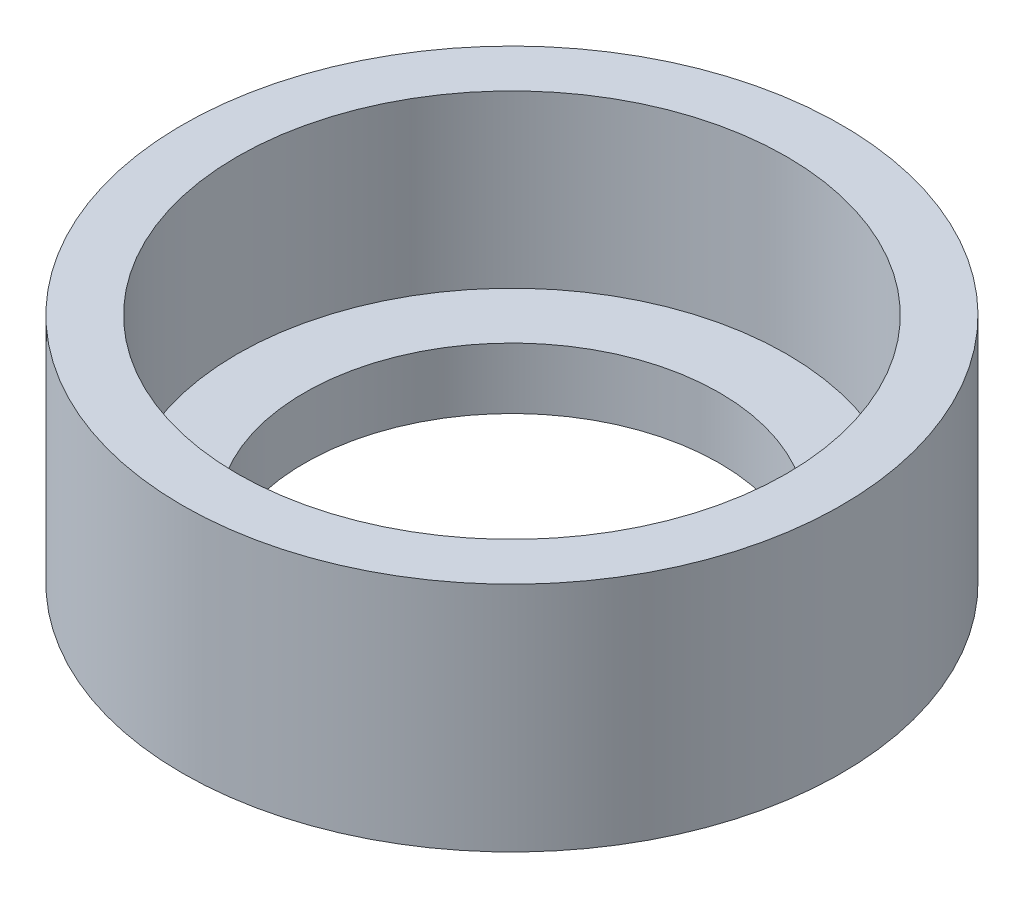
SolidWorks part; units mm, degrees
ref_plane "Front Plane" through (0, 0, 0) normal (0, 0, 1) x (1, 0, 0)
ref_plane "Top Plane" through (0, 0, 0) normal (0, 1, 0) x (1, 0, 0)
ref_plane "Right Plane" through (0, 0, 0) normal (1, 0, 0) x (0, 0, -1)
sketch "Sketch1" plane through (0, 0, 0) normal (0, 1, 0) x (1, 0, 0)
  circle A0 centre (0, 0) radius 13.5
  circle A1 centre (0, 0) radius 8.5
  dimension "D1" = 17
  dimension "D2" = 27
extrude "Boss-Extrude1" add sketch "Sketch1" along normal blind 9.5
sketch "Sketch2" plane through (0, 9.5, 0) normal (0, 1, 0) x (-1, 0, 0)
  circle A0 centre (0, 0) radius 11.25
  dimension "D1" = 22.5
extrude "Cut-Extrude1" cut sketch "Sketch2" against normal blind 7
